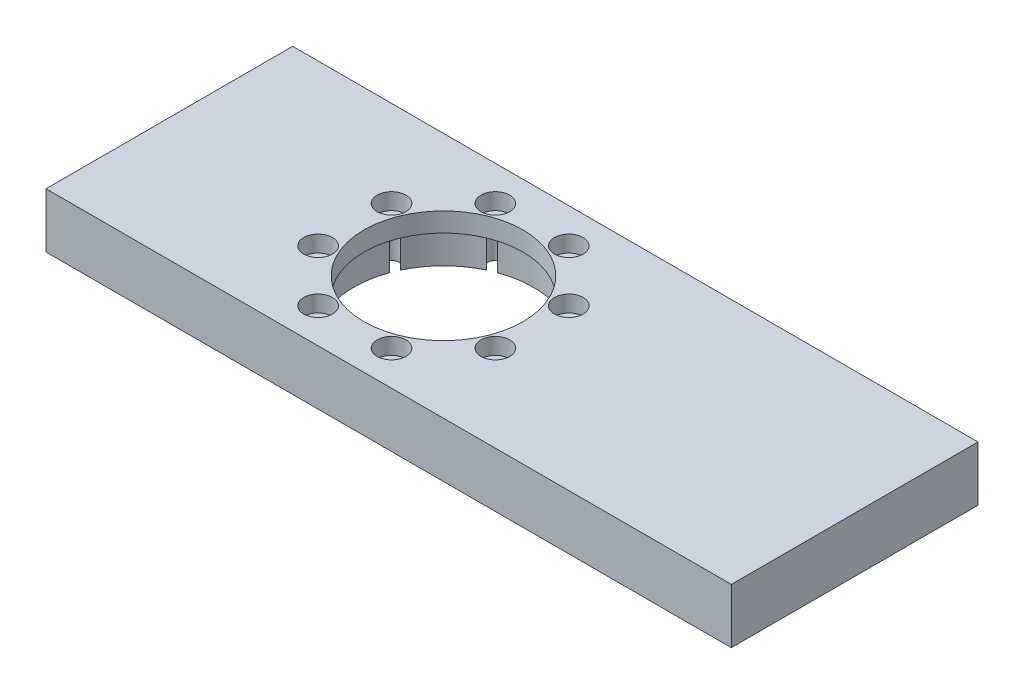
SolidWorks part; units mm, degrees
ref_plane "Front Plane" through (0, 0, 0) normal (0, 0, 1) x (1, 0, 0)
ref_plane "Top Plane" through (0, 0, 0) normal (0, 1, 0) x (1, 0, 0)
ref_plane "Right Plane" through (0, 0, 0) normal (1, 0, 0) x (0, 0, -1)
sketch "Sketch1" plane through (0, 0, 0) normal (0, 1, 0) x (1, 0, 0)
  line L0 (-122.4227, 0) -> (145.8763, 0) construction
  line L1 (-100, -45) -> (150, -45)
  line L2 (-100, -45) -> (-100, 45)
  line L3 (-100, 45) -> (150, 45)
  line L4 (150, -45) -> (150, 45)
  line L5 (0, 60.8647) -> (0, -60.4073) construction
  dimension "D1" = 90
  dimension "D2" = 100
  dimension "D3" = 150
extrude "Boss-Extrude1" add sketch "Sketch1" along normal blind 20
sketch "Sketch11" plane through (0, 20, 0) normal (0, 1, 0) x (1, 0, 0)
  line L0 (-148.058, 0) -> (133.5933, 0) construction
  line L1 (0, 55.3448) -> (0, -57.6508) construction
  line L2 (0, 0) -> (-40.9461, -16.9604) construction
  circle A0 centre (0, 0) radius 35 construction
  circle A1 centre (0, 0) radius 29
  point P5 (0, 0)
  point P8 (-32.3358, -13.3939)
  point P10 (-32.3358, 13.3939)
  point P11 (-148.058, 0)
  point P12 (-13.3939, 32.3358)
  point P19 (0, 0)
  point P20 (133.5933, 0)
  point P24 (0, 0)
  point P25 (13.3939, 32.3358)
  point P26 (32.3358, 13.3939)
  point P27 (32.3358, -13.3939)
  point P28 (13.3939, -32.3358)
  point P29 (-13.3939, -32.3358)
  dimension "D1" = 70
  dimension "D5" = 58
  dimension "D3" = 22.5
  dimension "D2" = 8
extrude "Cut-Extrude1" cut sketch "Sketch11" against normal through all both and the other way through all
hole_wizard "CBORE for M5 Hex Head Bolt2" positions "3DSketch11" profile "Sketch14" counterbore size "M5" standard "BSI" end condition through all
sketch3d "3DSketch11"
  point P0 (-32.3358, 20, -13.3939)
  point P3 (-13.3939, 20, -32.3358)
  point P6 (13.3939, 20, -32.3358)
  point P9 (32.3358, 20, -13.3939)
  point P12 (32.3358, 20, 13.3939)
  point P15 (13.3939, 20, 32.3358)
  point P18 (-13.3939, 20, 32.3358)
  point P21 (-32.3358, 20, 13.3939)
sketch "Sketch14" plane through (-32.3358, 20, -13.3939) normal (1, 0, 0) x (0, 0, 1)
  line L0 (0, 0) -> (0, 20)
  line L1 (0, 20) -> (2.75, 20)
  line L3 (2.75, 20) -> (2.75, 6)
  line L4 (2.75, 6) -> (5.25, 6)
  line L5 (5.25, 6) -> (5.25, 0)
  line L7 (5.25, 0) -> (0, 0)
  line L11 (0, -6.35) -> (0, 107.95) construction
  dimension "Thru Hole Dia." = 5.5
  dimension "Thru Hole Depth" = 20
  dimension "C'Bore Dia." = 10.5
  dimension "C'Bore Depth" = 6
sketch "Sketch15" plane through (0, 0, 0) normal (0, 1, 0) x (1, 0, 0)
  circle A0 centre (0, 0) radius 32.75
  dimension "D1" = 65.5
extrude "Cut-Extrude2" cut sketch "Sketch15" along normal blind 13
